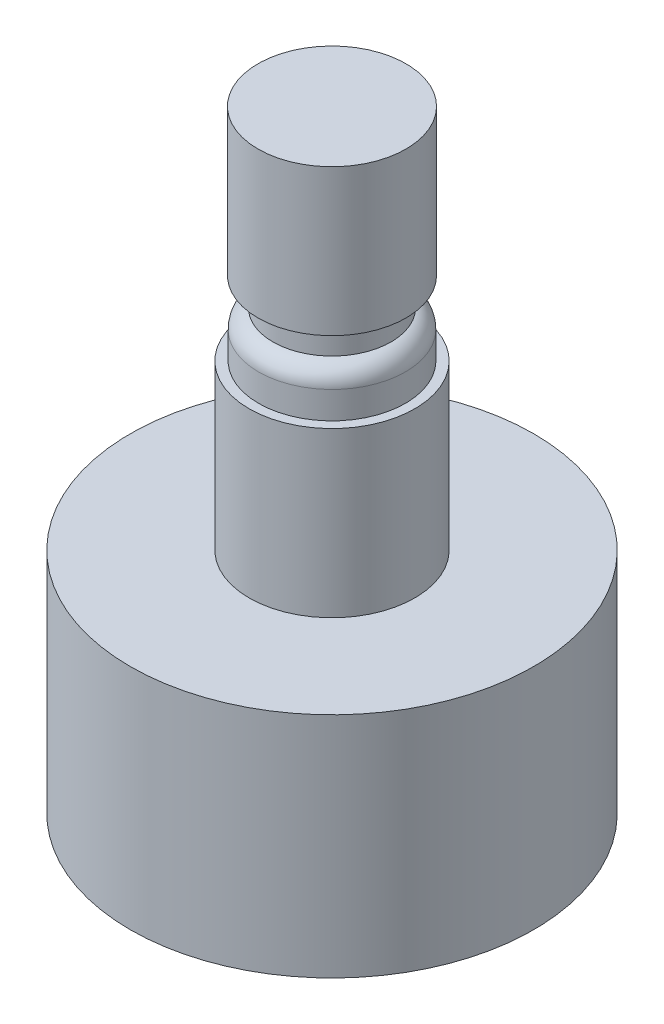
SolidWorks part; units mm, degrees
ref_plane "Front Plane" through (0, 0, 0) normal (0, 0, 1) x (1, 0, 0)
ref_plane "Top Plane" through (0, 0, 0) normal (0, 1, 0) x (1, 0, 0)
ref_plane "Right Plane" through (0, 0, 0) normal (1, 0, 0) x (0, 0, -1)
sketch "Sketch2" plane through (0, 0, 0) normal (0, 1, 0) x (1, 0, 0)
  circle A0 centre (0, 0) radius 8.1915
  dimension "D1" = 16.383
extrude "Boss-Extrude1" add sketch "Sketch2" along normal blind 9.2583
sketch "Sketch4" plane through (0, 9.2583, 0) normal (0, 1, 0) x (1, 0, 0)
  circle A0 centre (0, 0) radius 3.3655
  dimension "D1" = 6.731
extrude "Boss-Extrude3" add sketch "Sketch4" along normal blind 6.6548
sketch "Sketch5" plane through (0, 15.9131, 0) normal (0, 1, 0) x (1, 0, 0)
  circle A0 centre (0, 0) radius 2.9845
  dimension "D1" = 5.969
extrude "Boss-Extrude4" add sketch "Sketch5" along normal blind 1.8669
fillet "Fillet1" radius 0.762 1 edges at (0, 17.78, 2.9845)
sketch "Sketch7" plane through (0, 17.78, 0) normal (0, 1, 0) x (1, 0, 0)
  circle A0 centre (0, 0) radius 2.4003
  dimension "D1" = 4.8006
extrude "Boss-Extrude5" add sketch "Sketch7" along normal blind 1.143
sketch "Sketch8" plane through (0, 18.923, 0) normal (0, 1, 0) x (1, 0, 0)
  circle A0 centre (0, 0) radius 3.0035
  dimension "D1" = 6.0071
extrude "Boss-Extrude6" add sketch "Sketch8" along normal blind 5.9436
